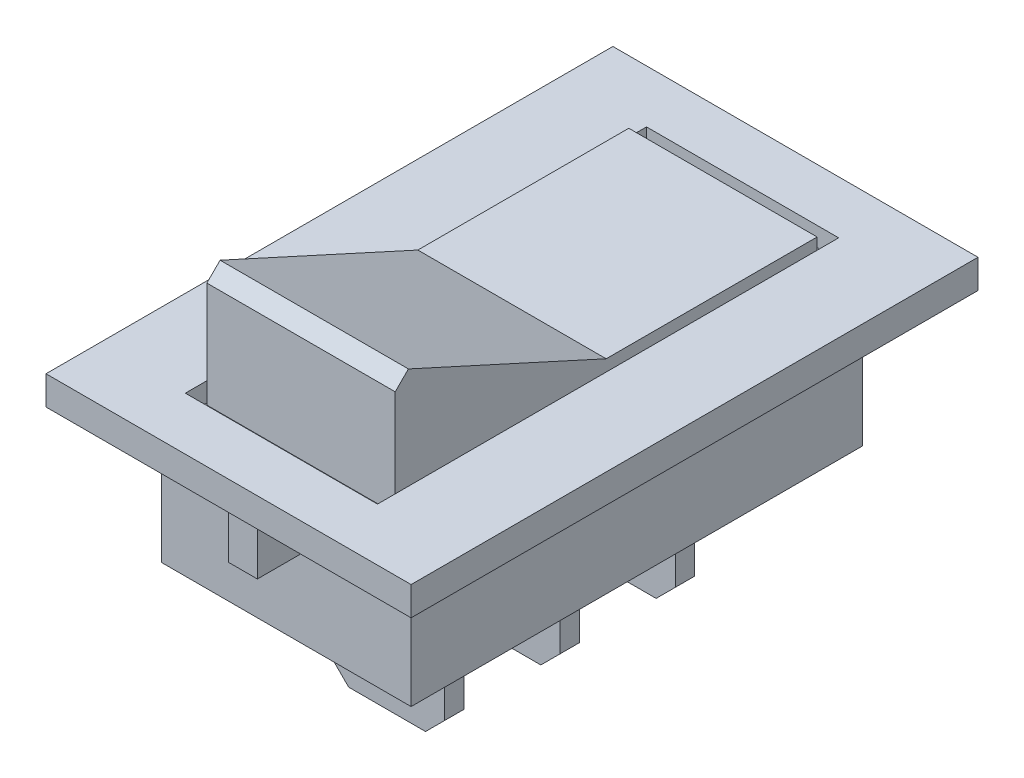
SolidWorks part; units mm, degrees
ref_plane "Front Plane" through (0, 0, 0) normal (0, 0, 1) x (1, 0, 0)
ref_plane "Top Plane" through (0, 0, 0) normal (0, 1, 0) x (1, 0, 0)
ref_plane "Right Plane" through (0, 0, 0) normal (1, 0, 0) x (0, 0, -1)
sketch "Sketch1" plane through (0, 0, 0) normal (0, 1, 0) x (1, 0, 0)
  line L0 (0.75, -11.75) -> (6.5, -11.75)
  line L1 (0.75, -14) -> (0.75, -11.75)
  line L2 (-0.75, -14) -> (0.75, -14)
  line L3 (-0.75, -11.75) -> (-0.75, -14)
  line L4 (-6.5, -11.75) -> (-0.75, -11.75)
  line L5 (6.5, -11.75) -> (6.5, 11.75)
  line L6 (6.5, 11.75) -> (0.75, 11.75)
  line L7 (0.75, 11.75) -> (0.75, 14)
  line L8 (0.75, 14) -> (-0.75, 14)
  line L9 (-0.75, 14) -> (-0.75, 11.75)
  line L10 (-0.75, 11.75) -> (-6.5, 11.75)
  line L11 (-6.5, 11.75) -> (-6.5, -11.75)
extrude "Boss-Extrude1" add sketch "Sketch1" against normal blind 3
sketch "Sketch2" plane through (0, -3, 0) normal (0, -1, 0) x (1, 0, 0)
  line L0 (-6.5, 11.75) -> (-0.75, 11.75) construction
  line L1 (-6.5, 11.75) -> (6.5, 11.75)
  line L2 (-6.5, 11.75) -> (-6.5, -11.75)
  line L3 (-6.5, -11.75) -> (6.5, -11.75)
  line L4 (6.5, 11.75) -> (6.5, -11.75)
  line L5 (-6.5, -11.75) -> (-6.5, 11.75) construction
extrude "Boss-Extrude2" add sketch "Sketch2" along normal blind 4
sketch "Sketch3" plane through (0, -7, 0) normal (0, -1, 0) x (1, 0, 0)
  line L0 (0, 0) -> (22.4927, 0) construction
  line L1 (3, 0.5) -> (-3, 0.5)
  line L2 (3, 0.5) -> (3, -0.5)
  line L3 (3, -0.5) -> (-3, -0.5)
  line L4 (-3, 0.5) -> (-3, -0.5)
  line L5 (3, 0.5) -> (-3, -0.5) construction
  line L6 (3, -0.5) -> (-3, 0.5) construction
  line L7 (0, 0) -> (0, 6) construction
  line L8 (3, 6.5) -> (-3, 6.5)
  line L9 (3, 6.5) -> (3, 5.5)
  line L10 (3, 5.5) -> (-3, 5.5)
  line L11 (-3, 6.5) -> (-3, 5.5)
  line L12 (3, 6.5) -> (-3, 5.5) construction
  line L13 (3, 5.5) -> (-3, 6.5) construction
  line L14 (3, -5.5) -> (-3, -6.5) construction
  line L15 (3, -6.5) -> (-3, -5.5) construction
  line L16 (-3, -6.5) -> (-3, -5.5)
  line L17 (3, -5.5) -> (-3, -5.5)
  line L18 (3, -6.5) -> (3, -5.5)
  line L19 (3, -6.5) -> (-3, -6.5)
  point P0 (0, 0)
  point P8 (0, 6)
  point P18 (0, -6)
  dimension "D1" = 1
  dimension "D2" = 6
  dimension "D3" = 6
  dimension "D4" = 6
extrude "Boss-Extrude3" add sketch "Sketch3" along normal blind 6
chamfer "Chamfer1" distance 1 angle 45 6 edges at (3, -13, -6) (-3, -13, -6) (3, -13, 0) (-3, -13, 0) (3, -13, 6) (-3, -13, 6)
sketch "Sketch4" plane through (0, 0, 0) normal (0, 1, 0) x (1, 0, 0)
  line L0 (-0.75, 11.75) -> (-6.5, 11.75) construction
  line L1 (-9.5, -14.75) -> (9.5, -14.75)
  line L2 (-9.5, -14.75) -> (-9.5, 14.75)
  line L3 (-9.5, 14.75) -> (9.5, 14.75)
  line L4 (9.5, -14.75) -> (9.5, 14.75)
  line L5 (-9.5, -14.75) -> (9.5, 14.75) construction
  line L6 (-9.5, 14.75) -> (9.5, -14.75) construction
  line L7 (-6.5, 11.75) -> (-6.5, -11.75) construction
  point P0 (0, 0)
  dimension "D1" = 3
  dimension "D2" = 3
extrude "Boss-Extrude4" add sketch "Sketch4" along normal blind 1.5
sketch "Sketch5" plane through (0, 1.5, 0) normal (0, 1, 0) x (1, 0, 0)
  line L1 (5, -12) -> (-5, -12)
  line L2 (5, -12) -> (5, 12)
  line L3 (5, 12) -> (-5, 12)
  line L4 (-5, -12) -> (-5, 12)
  line L5 (5, -12) -> (-5, 12) construction
  line L6 (5, 12) -> (-5, -12) construction
  point P0 (0, 0)
  dimension "D1" = 10
  dimension "D2" = 24
extrude "Cut-Extrude1" cut sketch "Sketch5" against normal blind 1
sketch "Sketch6" plane through (0, 0, 0) normal (1, 0, 0) x (0, 0, -1)
  line L0 (-10.9778, 0) -> (10.9778, 0)
  line L1 (-11.75, 0) -> (11.75, 0) construction
  line L2 (-10.9778, 0) -> (-10.9778, 7)
  line L3 (-10.9778, 7) -> (0, 2)
  line L4 (0, 2) -> (10.9778, 2)
  line L5 (10.9778, 2) -> (10.9778, 0)
  dimension "D1" = 7
  dimension "D2" = 2
extrude "Boss-Extrude5" add sketch "Sketch6" along normal blind 4.9 and the other way blind 4.9
chamfer "Chamfer2" distance 1 angle 45 1 edges at (0, 7, 10.9778)
